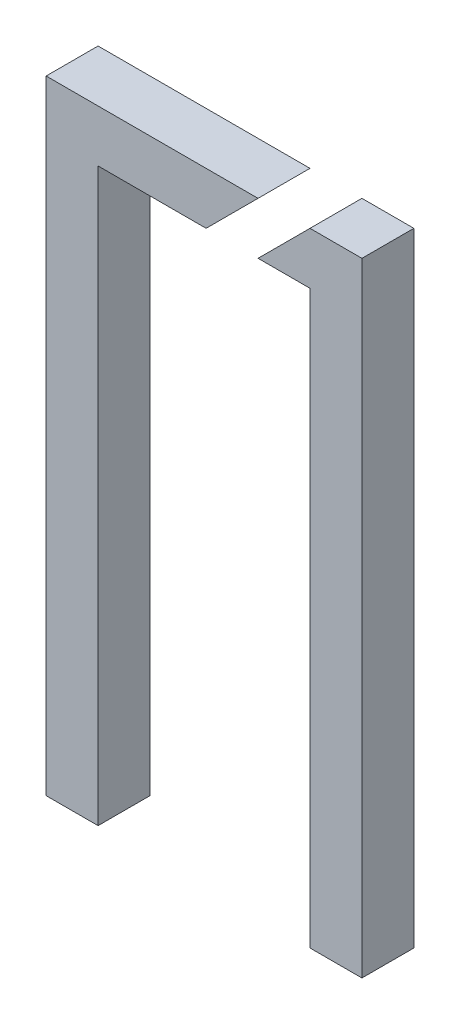
SolidWorks part; units mm, degrees
material "AISI 1020"
ref_plane "Front Plane" through (0, 0, 0) normal (0, 0, 1) x (1, 0, 0)
ref_plane "Top Plane" through (0, 0, 0) normal (0, 1, 0) x (1, 0, 0)
ref_plane "Right Plane" through (0, 0, 0) normal (1, 0, 0) x (0, 0, -1)
sketch "Sketch1" plane through (0, 0, 0) normal (0, 0, 1) x (1, 0, 0)
  line L0 (0, 6) -> (0, 0)
  line L1 (0, 6) -> (2.04, 6)
  line L2 (2.04, 6) -> (1.54, 5.5)
  line L3 (1.54, 5.5) -> (0.5, 5.5)
  line L4 (0.5, 5.5) -> (0.5, 0)
  line L5 (0.5, 0) -> (0, 0)
  line L6 (2.54, 6) -> (3.04, 6)
  line L7 (3.04, 6) -> (3.04, 0)
  line L8 (3.04, 0) -> (2.54, 0)
  line L9 (2.54, 0) -> (2.54, 5.5)
  line L10 (2.54, 5.5) -> (2.04, 5.5)
  line L11 (2.04, 5.5) -> (2.54, 6)
  point P9 (0.25, 0)
  point P14 (2.79, 0)
  dimension "D1" = 0.5
  dimension "D2" = 0.5
  dimension "D3" = 0.5
  dimension "D4" = 2.54
  dimension "D5" = 6
  dimension "D6" = 0.5
extrude "Boss-Extrude1" add sketch "Sketch1" along normal blind 0.5
sketch "Sketch3" plane through (0, 0, 0) normal (0, 1, 0) x (1, 0, 0)
  line L0 (0, -0.25) -> (3.04, -0.25) construction
  line L1 (0, -0.5) -> (0, 0) construction
  line L2 (3.04, -0.5) -> (3.04, 0) construction
  line L3 (1.54, -0.5) -> (1.54, 0) construction
  line L4 (2.04, -0.5) -> (0, -0.5) construction
  point P11 (0, 0)
sketch "Sketch7" plane through (0, 6, 0) normal (0, 1, 0) x (1, 0, 0)
  line L0 (0, -0.25) -> (3.04, -0.25) construction
  circle A0 centre (1.52, -0.25) radius 2.5 construction
  dimension "D1" = 5
